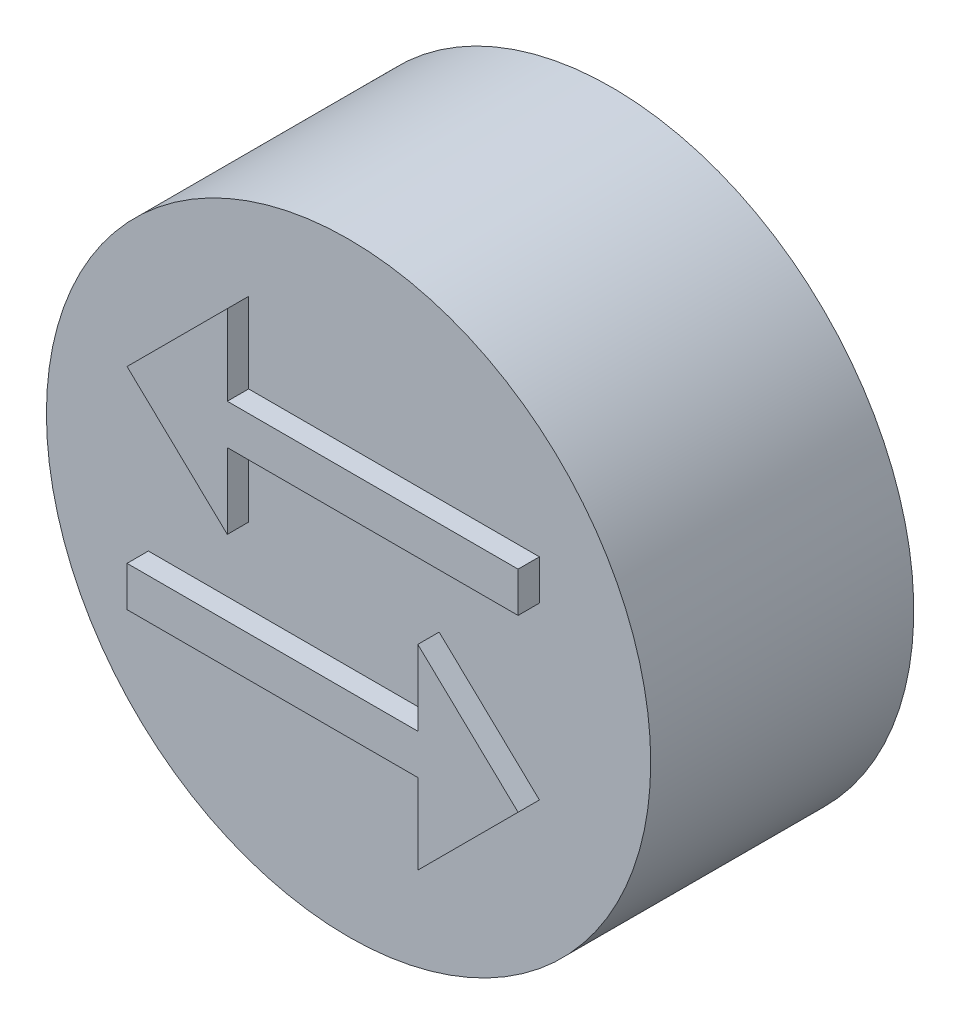
SolidWorks part; units mm, degrees
ref_plane "Front Plane" through (0, 0, 0) normal (0, 0, 1) x (1, 0, 0)
ref_plane "Top Plane" through (0, 0, 0) normal (0, 1, 0) x (1, 0, 0)
ref_plane "Right Plane" through (0, 0, 0) normal (1, 0, 0) x (0, 0, -1)
sketch "Sketch1" plane through (0, 0, 0) normal (0, 0, 1) x (1, 0, 0)
  circle A0 centre (0, 0) radius 8.5
  dimension "D1" = 17
extrude "Boss-Extrude1" add sketch "Sketch1" along normal blind 4.4
sketch "Sketch2" plane through (0, 0, 4.4) normal (0, 0, 1) x (1, 0, 0)
  line L19 (6.6377, 5.6994) -> (-3.7876, 5.6994) construction
  text T0 "D" font "Wingdings 3" height 11
  point P0 (6.6377, 5.6994)
  point P7 (3.2424, 1.1561)
  point P8 (6.4099, 5.3898)
  point P9 (0, 0)
  point P10 (7.712, 5.2328)
  point P11 (0, 0)
  point P12 (0, 0)
sketch "Sketch3" plane through (0, 0, 0) normal (0, 0, -1) x (-1, 0, 0)
  circle A0 centre (0, 0) radius 5.8
  dimension "D1" = 11.6
extrude "Cut-Extrude1" cut sketch "Sketch3" against normal blind 4
sketch "Sketch4" plane through (0, 0, 0) normal (0, 0, -1) x (-1, 0, 0)
  circle A1 centre (0, 0) radius 8.5
  circle A2 centre (0, 0) radius 8.5
  circle A4 centre (0, 0) radius 7.5
  dimension "D2" = 1
  dimension "D1" = 0
extrude "Boss-Extrude3" add sketch "Sketch4" along normal blind 3
sketch "Sketch6" plane through (0, 0, 0) normal (0, 1, 0) x (1, 0, 0)
  line L6 (7.5, 0) -> (5.8, -1.7)
  line L7 (5.8, -1.7) -> (5.8, 0)
  line L8 (5.8, 0) -> (7.5, 0)
  line L9 (7.5, 0) -> (-7.5, 0) construction
  line L10 (5.8, 0) -> (-5.8, 0) construction
  dimension "D1" = 45
ref_axis "Axis1" through (0, 0, -5.5) along (0, 0, 1)
revolve "Cut-Revolve1" cut sketch "Sketch6" angle 360 about axis through (0, 0, -5.5) along (0, 0, 1)
extrude "Boss-Extrude4" add sketch "Sketch2" along normal blind 0.6
